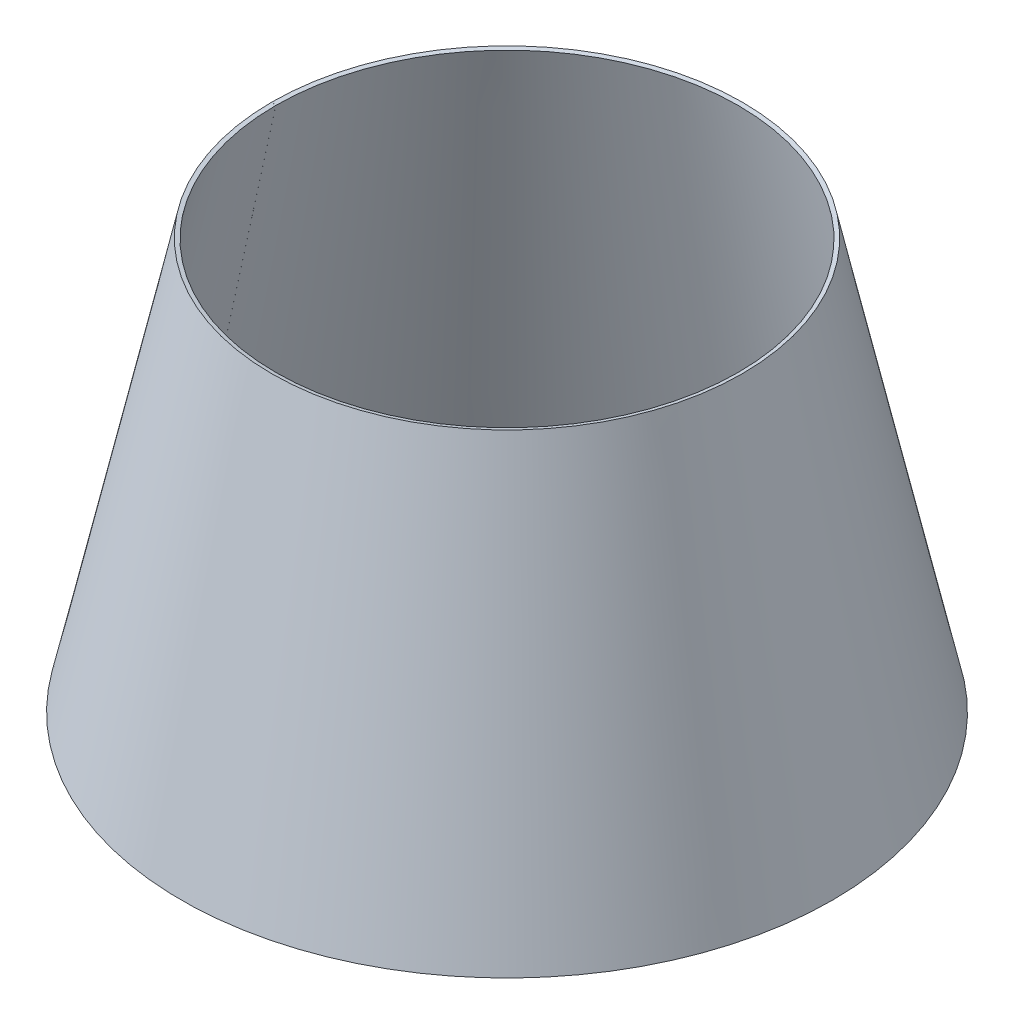
SolidWorks part; units mm, degrees
material "201 Annealed Stainless Steel (SS)"
ref_plane "Front Plane" through (0, 0, 0) normal (0, 0, 1) x (1, 0, 0)
ref_plane "Top Plane" through (0, 0, 0) normal (0, 1, 0) x (1, 0, 0)
ref_plane "Right Plane" through (0, 0, 0) normal (1, 0, 0) x (0, 0, -1)
sketch "Sketch1" plane through (0, 0, 0) normal (0, 0, 1) x (1, 0, 0)
  line L0 (-33.8636, 0) -> (-24.35, 43.25)
  line L1 (-33.8636, 0) -> (-34.2853, 0.0928)
  line L2 (-24.35, 43.25) -> (-24.7717, 43.3428)
  line L3 (-34.2853, 0.0928) -> (-24.7717, 43.3428)
  line L4 (0, 0) -> (0, 38.0052) construction
  dimension "D1" = 0.4318
  dimension "D2" = 43.25
  dimension "D3" = 33.8636
  dimension "D4" = 24.35
revolve "Revolve1" add sketch "Sketch1" angle 359.99 about L4
surface "Surface-Flatten1"
